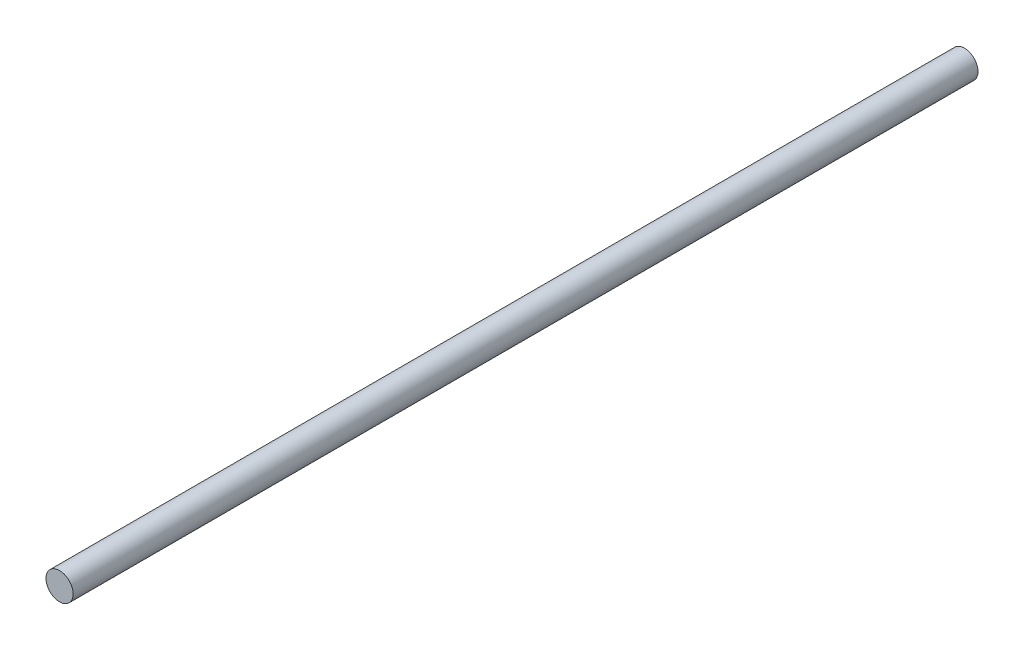
SolidWorks part; units mm, degrees
material "ABS generico"
ref_plane "Piano frontale" through (0, 0, 0) normal (0, 0, 1) x (1, 0, 0)
ref_plane "Piano superiore" through (0, 0, 0) normal (0, 1, 0) x (1, 0, 0)
ref_plane "Piano destro" through (0, 0, 0) normal (1, 0, 0) x (0, 0, -1)
sketch "Schizzo1" plane through (0, 0, 0) normal (0, 0, 1) x (1, 0, 0)
  circle A0 centre (0, 0) radius 1.5
  dimension "D1" = 3
extrude "Estrusione-Estrusione1" add sketch "Schizzo1" along normal blind 100
